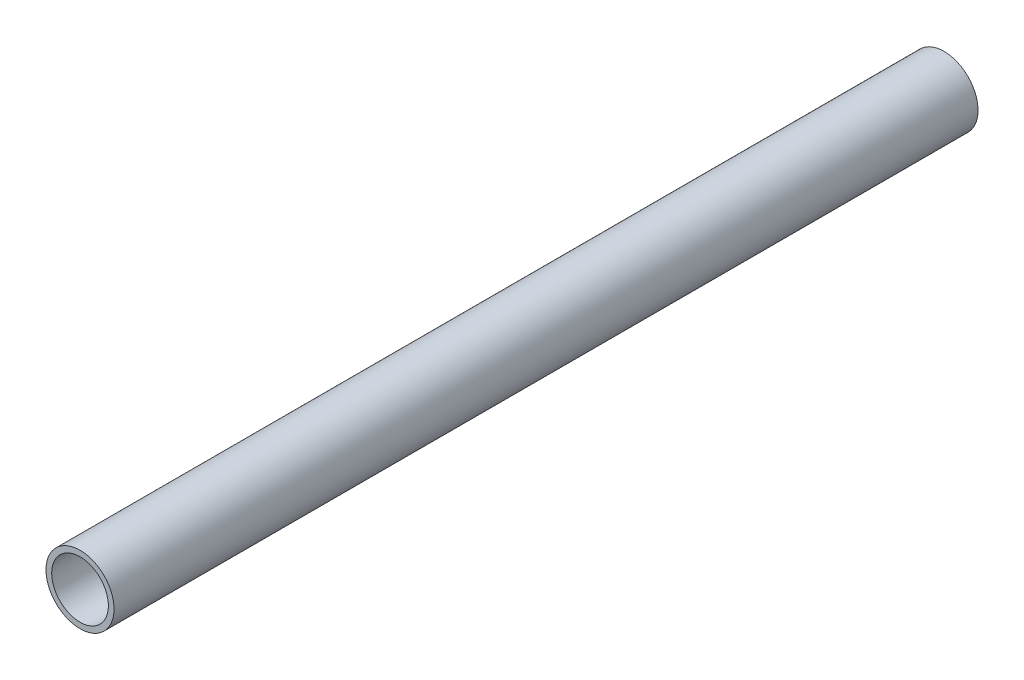
SolidWorks part; units mm, degrees
material "Thornel Mat VMA"
ref_plane "Front Plane" through (0, 0, 0) normal (0, 0, 1) x (1, 0, 0)
ref_plane "Top Plane" through (0, 0, 0) normal (0, 1, 0) x (1, 0, 0)
ref_plane "Right Plane" through (0, 0, 0) normal (1, 0, 0) x (0, 0, -1)
sketch "Sketch1" plane through (0, 0, 0) normal (0, 0, 1) x (1, 0, 0)
  circle A0 centre (0, 0) radius 3
  circle A1 centre (0, 0) radius 2.5
  dimension "D1" = 6
  dimension "D2" = 5
extrude "Boss-Extrude1" add sketch "Sketch1" along normal blind 76.2
